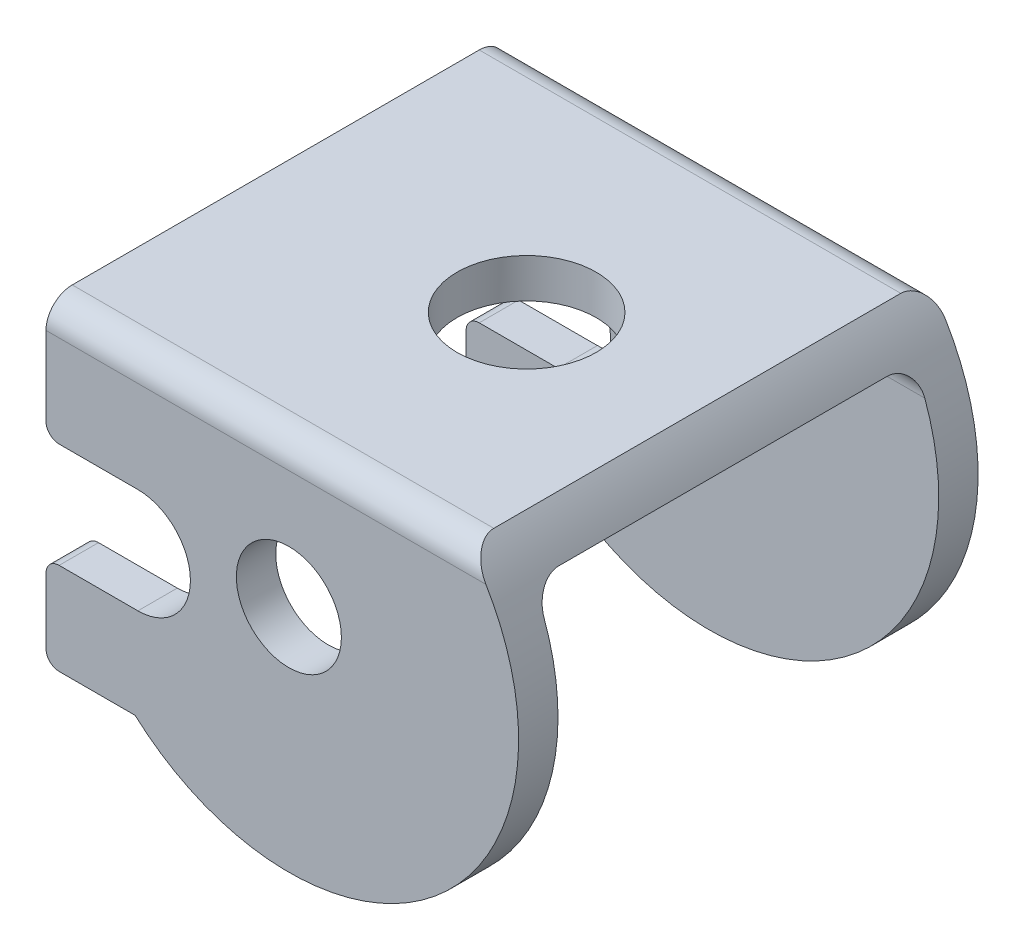
SolidWorks part; units mm, degrees
ref_plane "正面" through (0, 0, 0) normal (0, 0, 1) x (1, 0, 0)
ref_plane "平面" through (0, 0, 0) normal (0, 1, 0) x (1, 0, 0)
ref_plane "右側面" through (0, 0, 0) normal (1, 0, 0) x (0, 0, -1)
sketch "ｽｹｯﾁ1" plane through (0, 0, 0) normal (0, 0, 1) x (1, 0, 0)
  line L0 (-18.5, 11) -> (-18.5, -13)
  line L1 (-18.5, -13) -> (-11.7154, -13)
  line L2 (-18.5, 11) -> (13.6107, 11)
  arc A1 (-11.7154, -13) -> (13.6107, 11) centre (0, 0) ccw
  point P5 (-18.5, -9.2413)
  dimension "D4" = 11
  dimension "D3" = 18.5
  dimension "D2" = 35
  dimension "D1" = 24
extrude "ﾎﾞｽ - 押し出し1" add sketch "ｽｹｯﾁ1" along normal mid plane 35
sketch "ｽｹｯﾁ2" plane through (0, 0, 17.5) normal (0, 0, 1) x (1, 0, 0)
  line L0 (-18.5, 11) -> (-18.5, -13) construction
  line L1 (-18.5, 2) -> (-11.5, 2)
  line L2 (-18.5, 2) -> (-18.5, -6)
  line L3 (-18.5, -6) -> (-11.5, -6)
  line L5 (13.6107, 11) -> (-18.5, 11) construction
  arc A0 (-11.5, -6) -> (-11.5, 2) centre (-11.5, -2) ccw
  circle A1 centre (0, 0) radius 4
  dimension "D6" = 8
  dimension "D1" = 8
  dimension "D2" = 9
  dimension "D5" = 7
extrude "ｶｯﾄ - 押し出し1" cut sketch "ｽｹｯﾁ2" against normal through all
sketch "ｽｹｯﾁ3" plane through (-18.5, 0, 0) normal (-1, 0, 0) x (0, 0, 1)
  line L0 (-17.5, -17.5) -> (17.5, -17.5) construction
  line L1 (-14.5, 8) -> (14.5, 8)
  line L2 (-14.5, 8) -> (-14.5, -17.5)
  line L3 (-14.5, -17.5) -> (14.5, -17.5)
  line L4 (14.5, 8) -> (14.5, -17.5)
  line L5 (17.5, 11) -> (-17.5, 11) construction
  line L6 (17.5, -17.5) -> (17.5, 11) construction
  line L7 (-17.5, 11) -> (-17.5, -17.5) construction
  dimension "D1" = 3
  dimension "D2" = 3
  dimension "D3" = 3
extrude "ｶｯﾄ - 押し出し2" cut sketch "ｽｹｯﾁ3" against normal through all
sketch "ｽｹｯﾁ4" plane through (0, 11, 0) normal (0, 1, 0) x (1, 0, 0)
  line L0 (13.6107, -17.5) -> (13.6107, 17.5) construction
  circle A0 centre (0.6107, 0) radius 5.3
  dimension "D1" = 13
  dimension "D3" = 10.6
extrude "ｶｯﾄ - 押し出し3" cut sketch "ｽｹｯﾁ4" against normal up to next
fillet "ﾌｨﾚｯﾄ1" radius 1 6 edges at (-18.5, -13, -16) (-18.5, -13, 16) (-18.5, -6, -16) (-18.5, -6, 16) (-18.5, 2, -16) (-18.5, 2, 16)
fillet "ﾌｨﾚｯﾄ2" radius 2 4 edges at (-1.4678, 8, -14.5) (-1.4678, 8, 14.5) (-2.4447, 11, -17.5) (-2.4447, 11, 17.5)
